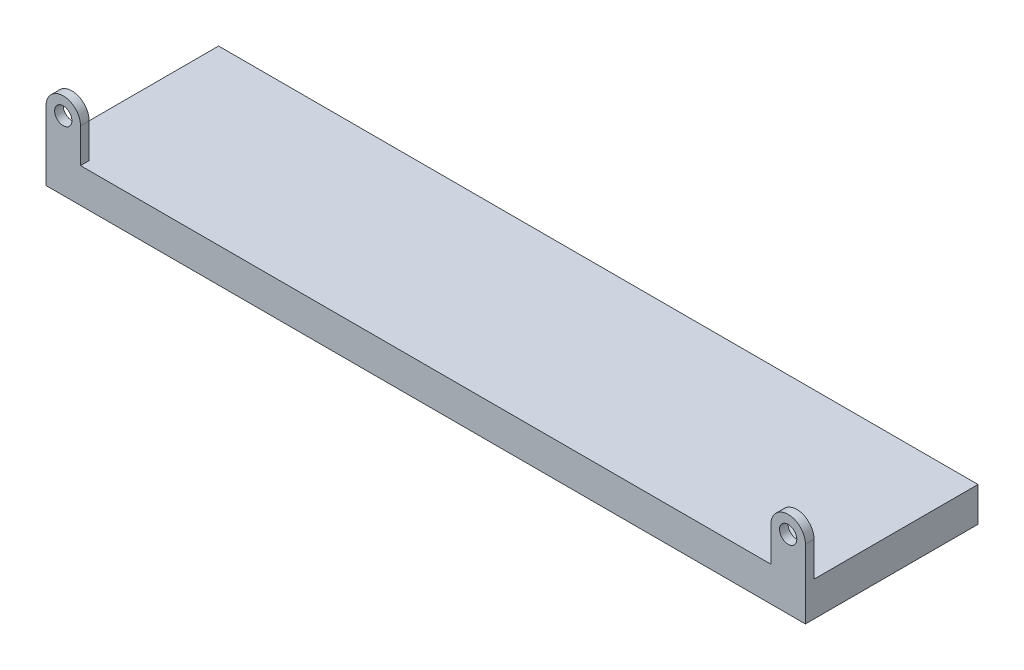
SolidWorks part; units mm, degrees
material "Plain Carbon Steel"
ref_plane "Front Plane" through (0, 0, 0) normal (0, 0, 1) x (1, 0, 0)
ref_plane "Top Plane" through (0, 0, 0) normal (0, 1, 0) x (1, 0, 0)
ref_plane "Right Plane" through (0, 0, 0) normal (1, 0, 0) x (0, 0, -1)
sketch "Sketch1" plane through (0, 0, 0) normal (0, 0, 1) x (1, 0, 0)
  line L0 (0, 0) -> (2667, 0)
  line L1 (-63.5, 0) -> (63.5, 0)
  line L2 (-63.5, 0) -> (-63.5, -127)
  line L3 (-63.5, -127) -> (63.5, -127)
  line L4 (63.5, 0) -> (63.5, -127)
  line L6 (2730.5, 0) -> (2603.5, 0)
  line L7 (2730.5, 0) -> (2730.5, -127)
  line L8 (2730.5, -127) -> (2603.5, -127)
  line L9 (2603.5, 0) -> (2603.5, -127)
  circle A0 centre (0, 0) radius 63.5
  circle A1 centre (2667, 0) radius 63.5
  dimension "D1" = 127
  dimension "D2" = 2667
  dimension "D3" = 127
  dimension "D4" = 127
  dimension "D5" = 127
extrude "Boss-Extrude1" add sketch "Sketch1" against normal blind 31.75 contours L6 A1 L0 | L0 A1 L6 | A1 L9 L8 L7 | L0 A0 L1
sketch "Sketch2" plane through (0, 0, 0) normal (0, 0, 1) x (1, 0, 0)
  line L0 (2730.5, 0) -> (2730.5, -127) construction
  line L1 (-63.5, -127) -> (2730.5, -127)
  line L2 (-63.5, -127) -> (-63.5, -254)
  line L3 (-63.5, -254) -> (2730.5, -254)
  line L4 (2730.5, -127) -> (2730.5, -254)
  dimension "D1" = 127
extrude "Boss-Extrude2" add sketch "Sketch2" against normal blind 635
sketch "Sketch3" plane through (0, 0, 0) normal (0, 0, 1) x (1, 0, 0)
  circle A0 centre (0, 0) radius 31.75
  circle A1 centre (2667, 0) radius 31.75
  dimension "D1" = 63.5
extrude "Cut-Extrude1" cut sketch "Sketch3" against normal through all
